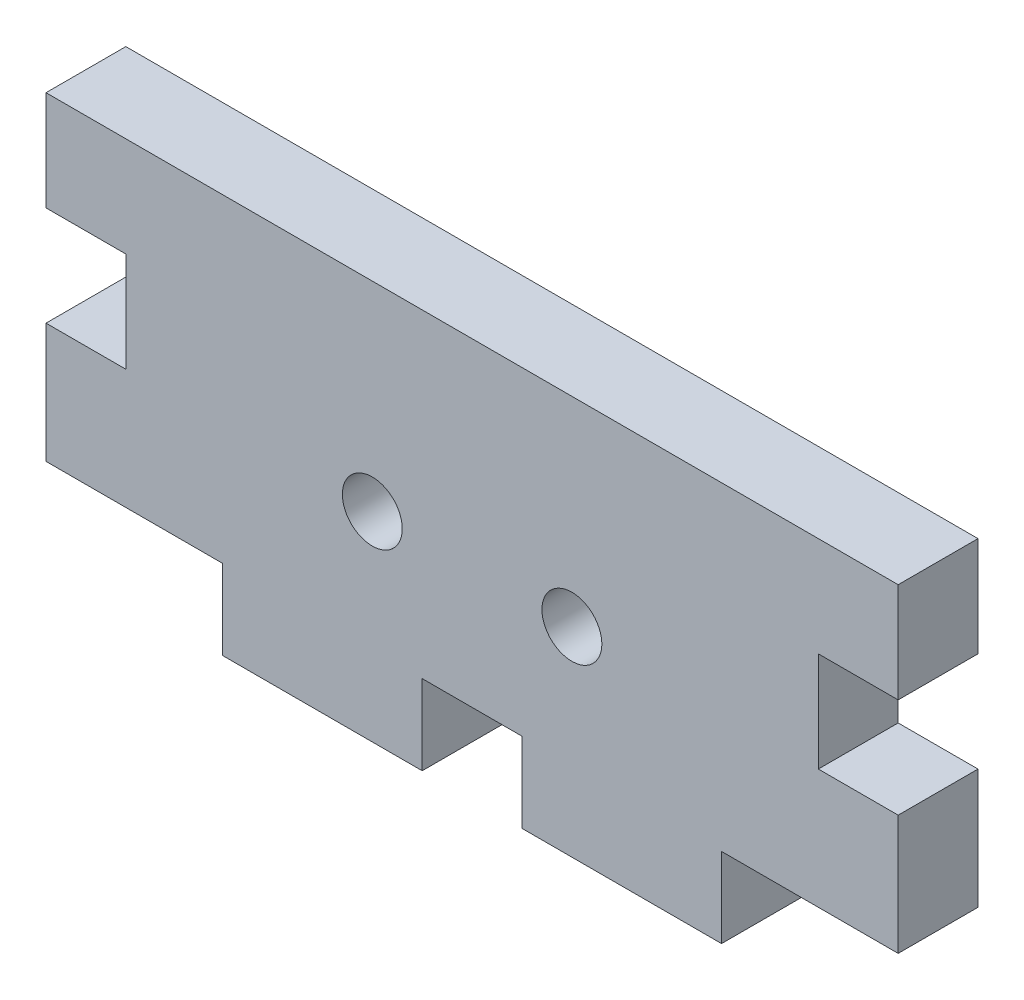
SolidWorks part; units mm, degrees
ref_plane "Спереди" through (0, 0, 0) normal (0, 0, 1) x (1, 0, 0)
ref_plane "Сверху" through (0, 0, 0) normal (0, 1, 0) x (1, 0, 0)
ref_plane "Справа" through (0, 0, 0) normal (1, 0, 0) x (0, 0, -1)
other "Configuration Table"
sketch "Эскиз1" plane through (0, 0, 0) normal (0, 0, 1) x (1, 0, 0)
  line L1 (0, 0) -> (42.7, 0)
  line L2 (0, 0) -> (0, 20)
  line L3 (0, 20) -> (42.7, 20)
  line L4 (42.7, 0) -> (42.7, 20)
  dimension "D1" = 20
  dimension "D2" = 42.7
extrude "Бобышка-Вытянуть1" add sketch "Эскиз1" along normal blind 4
sketch "Эскиз2" plane through (0, 0, 4) normal (0, 0, 1) x (1, 0, 0)
  line L0 (21.35, 20) -> (21.35, 0) construction
  line L1 (0, 0) -> (8.85, 0)
  line L2 (0, 0) -> (0, 4)
  line L3 (0, 4) -> (8.85, 4)
  line L4 (8.85, 0) -> (8.85, 4)
  line L5 (42.7, 20) -> (0, 20) construction
  line L6 (0, 0) -> (42.7, 0) construction
  line L7 (23.85, 0) -> (18.85, 0)
  line L8 (18.85, 0) -> (18.85, 4)
  line L9 (18.85, 4) -> (23.85, 4)
  line L10 (23.85, 0) -> (23.85, 4)
  line L11 (33.85, 0) -> (33.85, 4)
  line L12 (42.7, 4) -> (33.85, 4)
  line L13 (42.7, 0) -> (42.7, 4)
  line L14 (42.7, 0) -> (33.85, 0)
  line L15 (0, 20) -> (0, 0) construction
  line L16 (0, 15) -> (4, 15)
  line L17 (0, 15) -> (0, 10)
  line L18 (0, 10) -> (4, 10)
  line L19 (4, 15) -> (4, 10)
  line L20 (42.7, 10) -> (38.7, 10)
  line L21 (38.7, 15) -> (38.7, 10)
  line L22 (42.7, 15) -> (38.7, 15)
  line L23 (42.7, 15) -> (42.7, 10)
  circle A0 centre (16.35, 10) radius 1.5
  circle A1 centre (26.35, 10) radius 1.5
  point P15 (21.35, 4)
  dimension "D1" = 10
  dimension "D2" = 5
  dimension "D3" = 4
  dimension "D4" = 4
  dimension "D5" = 5
  dimension "D6" = 5
extrude "Вырез-Вытянуть1" cut sketch "Эскиз2" against normal blind 4
